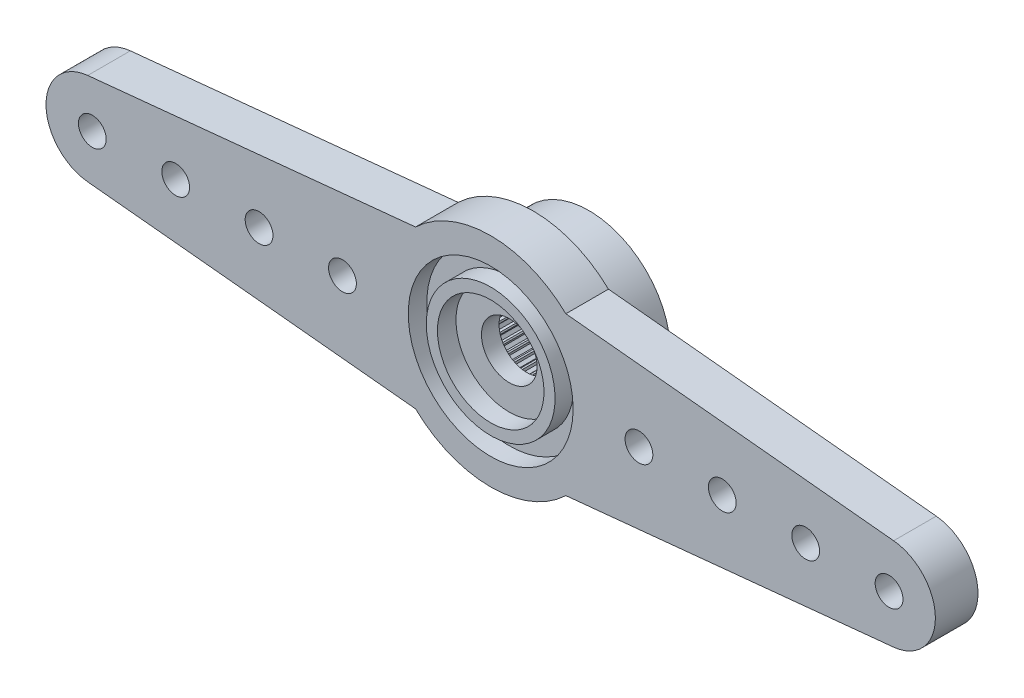
SolidWorks part; units mm, degrees
ref_plane "Plan de face" through (0, 0, 0) normal (0, 0, 1) x (1, 0, 0)
ref_plane "Plan de dessus" through (0, 0, 0) normal (0, 1, 0) x (1, 0, 0)
ref_plane "Plan de droite" through (0, 0, 0) normal (1, 0, 0) x (0, 0, -1)
sketch "Esquisse1" plane through (0, 0, 0) normal (0, 0, 1) x (1, 0, 0)
  line L0 (-21.5, 0) -> (0, 0) construction
  line L1 (-4.0562, 4.25) -> (-4.0562, -4.25) construction
  line L2 (-21.7478, 2.4877) -> (-4.0562, 4.25)
  line L3 (-21.7478, -2.4877) -> (-4.0562, -4.25)
  line L4 (0, 0) -> (0, 5.875) construction
  line L5 (21.7478, -2.4877) -> (4.0562, -4.25)
  line L6 (21.7478, 2.4877) -> (4.0562, 4.25)
  arc A0 (-4.0562, -4.25) -> (4.0562, -4.25) centre (0, 0) ccw
  arc A3 (-21.7478, 2.4877) -> (-21.7478, -2.4877) centre (-21.5, 0) ccw
  arc A4 (21.7478, 2.4877) -> (21.7478, -2.4877) centre (21.5, 0) cw
  arc A5 (4.0562, 4.25) -> (-4.0562, 4.25) centre (0, 0) ccw
  point P3 (0, 0)
  dimension "D1" = 11.75
  dimension "D2" = 2.5
  dimension "D3" = 43
  dimension "D5" = 8.5
extrude "Boss.-Extru.1" add sketch "Esquisse1" along normal blind 2.3
sketch "Esquisse2" plane through (0, 0, 2.3) normal (0, 0, 1) x (1, 0, 0)
  circle A0 centre (0, 0) radius 4.45
  dimension "D1" = 8.9
extrude "Enlèv. mat.-Extru.1" cut sketch "Esquisse2" against normal blind 1
sketch "Esquisse3" plane through (0, 0, 1.3) normal (0, 0, 1) x (1, 0, 0)
  circle A0 centre (0, 0) radius 2.875
  circle A1 centre (0, 0) radius 3.475
  dimension "D1" = 5.75
  dimension "D2" = 0.6
extrude "Boss.-Extru.2" add sketch "Esquisse3" along normal up to surface (1 mm away) up to face at (4.45, 0, 2.3)
sketch "Esquisse4" plane through (0, 0, 0) normal (0, 0, -1) x (-1, 0, 0)
  circle A0 centre (0, 0) radius 4.4
  dimension "D1" = 8.8
extrude "Boss.-Extru.3" add sketch "Esquisse4" along normal blind 3
sketch "Esquisse5" plane through (0, 0, 1.3) normal (0, 0, 1) x (1, 0, 0)
  circle A0 centre (0, 0) radius 1.5
  dimension "D1" = 3
extrude "Enlèv. mat.-Extru.2" cut sketch "Esquisse5" against normal through all
sketch "Esquisse6" plane through (0, 0, -3) normal (0, 0, -1) x (-1, 0, 0)
  line L0 (-0.1143, 2.9978) -> (-0.0406, 2.8652)
  line L1 (0.0406, 2.8652) -> (0.1143, 2.9978)
  line L2 (0, 2.8652) -> (0, 0) construction
  line L3 (-0.0406, 2.8652) -> (0.0406, 2.8652)
  line L4 (0.439, 2.8316) -> (0.5304, 2.9527)
  line L5 (0.3041, 2.9846) -> (0.3585, 2.8429)
  line L6 (0.3585, 2.8429) -> (0.439, 2.8316)
  line L7 (0.8288, 2.743) -> (0.9362, 2.8502)
  line L8 (0.7165, 2.9132) -> (0.7507, 2.7654)
  line L9 (0.7507, 2.7654) -> (0.8288, 2.743)
  line L10 (1.2025, 2.6009) -> (1.3237, 2.6922)
  line L11 (1.1149, 2.7851) -> (1.1283, 2.634)
  line L12 (1.1283, 2.634) -> (1.2025, 2.6009)
  line L13 (1.5527, 2.4083) -> (1.6855, 2.4817)
  line L14 (1.4917, 2.6029) -> (1.4839, 2.4513)
  line L15 (1.4839, 2.4513) -> (1.5527, 2.4083)
  line L16 (1.8728, 2.1687) -> (2.0145, 2.223)
  line L17 (1.8394, 2.3699) -> (1.8106, 2.2209)
  line L18 (1.8106, 2.2209) -> (1.8728, 2.1687)
  line L19 (2.1564, 1.887) -> (2.3043, 1.921)
  line L20 (2.1514, 2.0909) -> (2.1021, 1.9473)
  line L21 (2.1021, 1.9473) -> (2.1564, 1.887)
  line L22 (2.398, 1.5685) -> (2.5492, 1.5816)
  line L23 (2.4214, 1.7711) -> (2.3526, 1.6358)
  line L24 (2.3526, 1.6358) -> (2.398, 1.5685)
  line L25 (2.593, 1.2195) -> (2.7445, 1.2114)
  line L26 (2.6443, 1.4169) -> (2.5574, 1.2925)
  line L27 (2.5574, 1.2925) -> (2.593, 1.2195)
  line L28 (2.7375, 0.8468) -> (2.8864, 0.8177)
  line L29 (2.8158, 1.0351) -> (2.7124, 0.924)
  line L30 (2.7124, 0.924) -> (2.7375, 0.8468)
  line L31 (2.8287, 0.4575) -> (2.9721, 0.408)
  line L32 (2.9324, 0.6331) -> (2.8146, 0.5375)
  line L33 (2.8146, 0.5375) -> (2.8287, 0.4575)
  line L34 (2.8648, 0.0594) -> (3, -0.0096)
  line L35 (2.992, 0.2188) -> (2.862, 0.1406)
  line L36 (2.862, 0.1406) -> (2.8648, 0.0594)
  line L37 (2.8452, -0.3399) -> (2.9695, -0.427)
  line L38 (2.9933, -0.1997) -> (2.8537, -0.2591)
  line L39 (2.8537, -0.2591) -> (2.8452, -0.3399)
  line L40 (2.7702, -0.7325) -> (2.8811, -0.8361)
  line L41 (2.9364, -0.6144) -> (2.7899, -0.6537)
  line L42 (2.7899, -0.6537) -> (2.7702, -0.7325)
  line L43 (2.6413, -1.111) -> (2.7367, -1.229)
  line L44 (2.8223, -1.017) -> (2.6717, -1.0357)
  line L45 (2.6717, -1.0357) -> (2.6413, -1.111)
  line L46 (2.461, -1.4677) -> (2.5391, -1.5979)
  line L47 (2.6533, -1.3999) -> (2.5016, -1.3974)
  line L48 (2.5016, -1.3974) -> (2.461, -1.4677)
  line L49 (2.2328, -1.796) -> (2.292, -1.9357)
  line L50 (2.4327, -1.7556) -> (2.2828, -1.732)
  line L51 (2.2828, -1.732) -> (2.2328, -1.796)
  line L52 (1.9611, -2.0892) -> (2.0003, -2.2358)
  line L53 (2.1647, -2.0771) -> (2.0195, -2.0328)
  line L54 (2.0195, -2.0328) -> (1.9611, -2.0892)
  line L55 (1.6512, -2.3418) -> (1.6696, -2.4925)
  line L56 (1.8545, -2.3581) -> (1.7169, -2.2941)
  line L57 (1.7169, -2.2941) -> (1.6512, -2.3418)
  line L58 (1.3093, -2.5488) -> (1.3065, -2.7006)
  line L59 (1.5083, -2.5933) -> (1.381, -2.5107)
  line L60 (1.381, -2.5107) -> (1.3093, -2.5488)
  line L61 (0.9418, -2.7063) -> (0.9179, -2.8561)
  line L62 (1.1327, -2.7779) -> (1.0181, -2.6785)
  line L63 (1.0181, -2.6785) -> (0.9418, -2.7063)
  line L64 (0.556, -2.811) -> (0.5115, -2.9561)
  line L65 (0.7351, -2.9086) -> (0.6354, -2.7941)
  line L66 (0.6354, -2.7941) -> (0.556, -2.811)
  line L67 (0.1594, -2.861) -> (0.0951, -2.9985)
  line L68 (0.3231, -2.9825) -> (0.2404, -2.8553)
  line L69 (0.2404, -2.8553) -> (0.1594, -2.861)
  line L70 (-0.2404, -2.8553) -> (-0.3231, -2.9825)
  line L71 (-0.0951, -2.9985) -> (-0.1594, -2.861)
  line L72 (-0.1594, -2.861) -> (-0.2404, -2.8553)
  line L73 (-0.6354, -2.7941) -> (-0.7351, -2.9086)
  line L74 (-0.5115, -2.9561) -> (-0.556, -2.811)
  line L75 (-0.556, -2.811) -> (-0.6354, -2.7941)
  line L76 (-1.0181, -2.6785) -> (-1.1327, -2.7779)
  line L77 (-0.9179, -2.8561) -> (-0.9418, -2.7063)
  line L78 (-0.9418, -2.7063) -> (-1.0181, -2.6785)
  line L79 (-1.381, -2.5107) -> (-1.5083, -2.5933)
  line L80 (-1.3065, -2.7006) -> (-1.3093, -2.5488)
  line L81 (-1.3093, -2.5488) -> (-1.381, -2.5107)
  line L82 (-1.7169, -2.2941) -> (-1.8545, -2.3581)
  line L83 (-1.6696, -2.4925) -> (-1.6512, -2.3418)
  line L84 (-1.6512, -2.3418) -> (-1.7169, -2.2941)
  line L85 (-2.0195, -2.0328) -> (-2.1647, -2.0771)
  line L86 (-2.0003, -2.2358) -> (-1.9611, -2.0892)
  line L87 (-1.9611, -2.0892) -> (-2.0195, -2.0328)
  line L88 (-2.2828, -1.732) -> (-2.4327, -1.7556)
  line L89 (-2.292, -1.9357) -> (-2.2328, -1.796)
  line L90 (-2.2328, -1.796) -> (-2.2828, -1.732)
  line L91 (-2.5016, -1.3974) -> (-2.6533, -1.3999)
  line L92 (-2.5391, -1.5979) -> (-2.461, -1.4677)
  line L93 (-2.461, -1.4677) -> (-2.5016, -1.3974)
  line L94 (-2.6717, -1.0357) -> (-2.8223, -1.017)
  line L95 (-2.7367, -1.229) -> (-2.6413, -1.111)
  line L96 (-2.6413, -1.111) -> (-2.6717, -1.0357)
  line L97 (-2.7899, -0.6537) -> (-2.9364, -0.6144)
  line L98 (-2.8811, -0.8361) -> (-2.7702, -0.7325)
  line L99 (-2.7702, -0.7325) -> (-2.7899, -0.6537)
  line L100 (-2.8537, -0.2591) -> (-2.9933, -0.1997)
  line L101 (-2.9695, -0.427) -> (-2.8452, -0.3399)
  line L102 (-2.8452, -0.3399) -> (-2.8537, -0.2591)
  line L103 (-2.862, 0.1406) -> (-2.992, 0.2188)
  line L104 (-3, -0.0096) -> (-2.8648, 0.0594)
  line L105 (-2.8648, 0.0594) -> (-2.862, 0.1406)
  line L106 (-2.8146, 0.5375) -> (-2.9324, 0.6331)
  line L107 (-2.9721, 0.408) -> (-2.8287, 0.4575)
  line L108 (-2.8287, 0.4575) -> (-2.8146, 0.5375)
  line L109 (-2.7124, 0.924) -> (-2.8158, 1.0351)
  line L110 (-2.8864, 0.8177) -> (-2.7375, 0.8468)
  line L111 (-2.7375, 0.8468) -> (-2.7124, 0.924)
  line L112 (-2.5574, 1.2925) -> (-2.6443, 1.4169)
  line L113 (-2.7445, 1.2114) -> (-2.593, 1.2195)
  line L114 (-2.593, 1.2195) -> (-2.5574, 1.2925)
  line L115 (-2.3526, 1.6358) -> (-2.4214, 1.7711)
  line L116 (-2.5492, 1.5816) -> (-2.398, 1.5685)
  line L117 (-2.398, 1.5685) -> (-2.3526, 1.6358)
  line L118 (-2.1021, 1.9473) -> (-2.1514, 2.0909)
  line L119 (-2.3043, 1.921) -> (-2.1564, 1.887)
  line L120 (-2.1564, 1.887) -> (-2.1021, 1.9473)
  line L121 (-1.8106, 2.2209) -> (-1.8394, 2.3699)
  line L122 (-2.0145, 2.223) -> (-1.8728, 2.1687)
  line L123 (-1.8728, 2.1687) -> (-1.8106, 2.2209)
  line L124 (-1.4839, 2.4513) -> (-1.4917, 2.6029)
  line L125 (-1.6855, 2.4817) -> (-1.5527, 2.4083)
  line L126 (-1.5527, 2.4083) -> (-1.4839, 2.4513)
  line L127 (-1.1283, 2.634) -> (-1.1149, 2.7851)
  line L128 (-1.3237, 2.6922) -> (-1.2025, 2.6009)
  line L129 (-1.2025, 2.6009) -> (-1.1283, 2.634)
  line L130 (-0.7507, 2.7654) -> (-0.7165, 2.9132)
  line L131 (-0.9362, 2.8502) -> (-0.8288, 2.743)
  line L132 (-0.8288, 2.743) -> (-0.7507, 2.7654)
  line L133 (-0.3585, 2.8429) -> (-0.3041, 2.9846)
  line L134 (-0.5304, 2.9527) -> (-0.439, 2.8316)
  line L135 (-0.439, 2.8316) -> (-0.3585, 2.8429)
  circle A0 centre (0, 0) radius 3
  point P187 (0, 0)
  dimension "D1" = 6
  dimension "D2" = 45
extrude "Enlèv. mat.-Extru.3" cut sketch "Esquisse6" against normal blind 3.35
sketch "Esquisse7" plane through (0, 0, 2.3) normal (0, 0, 1) x (1, 0, 0)
  line L2 (0, -2.915) -> (0, 2.915) construction
  circle A0 centre (-21.5, 0) radius 0.75
  circle A7 centre (-17, 0) radius 0.75
  circle A8 centre (-12.5, 0) radius 0.75
  circle A9 centre (-8, 0) radius 0.75
  circle A10 centre (8, 0) radius 0.75
  circle A11 centre (12.5, 0) radius 0.75
  circle A12 centre (17, 0) radius 0.75
  circle A13 centre (21.5, 0) radius 0.75
  dimension "D1" = 1.5
  dimension "D2" = 4
extrude "Enlèv. mat.-Extru.4" cut sketch "Esquisse7" against normal blind 3.35
